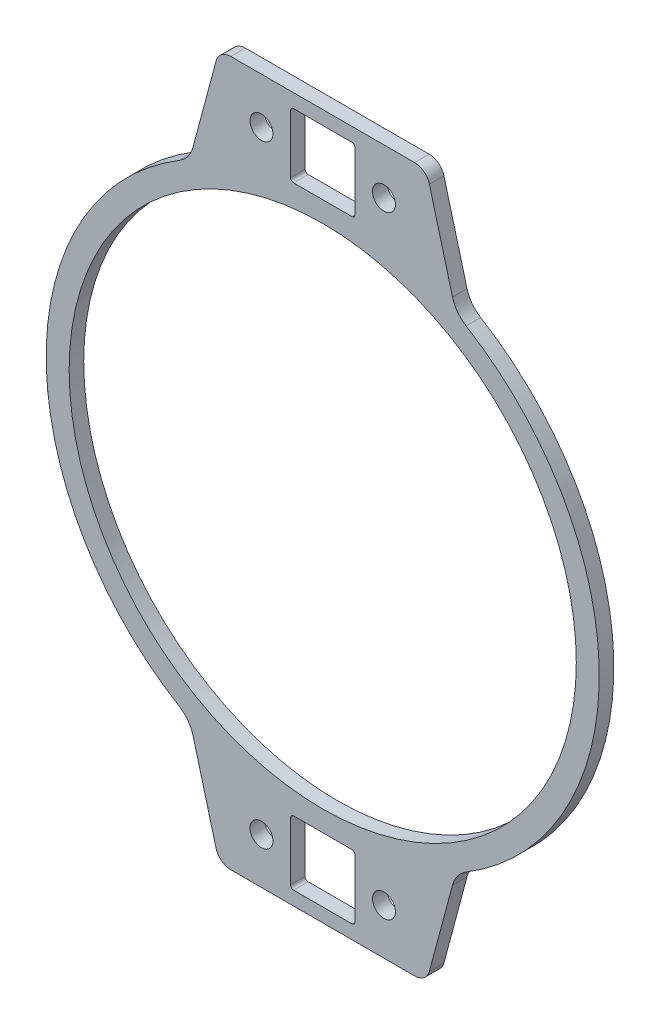
SolidWorks part; units mm, degrees
ref_plane "Front Plane" through (0, 0, 0) normal (0, 0, 1) x (1, 0, 0)
ref_plane "Top Plane" through (0, 0, 0) normal (0, 1, 0) x (1, 0, 0)
ref_plane "Right Plane" through (0, 0, 0) normal (1, 0, 0) x (0, 0, -1)
sketch "Sketch2" plane through (0, 0, -109.855) normal (0, 0, 1) x (1, 0, 0)
  line L6 (34.8296, -111.2941) -> (45.4142, -71.792)
  line L7 (-30, -115) -> (30, -115)
  line L8 (-45.4142, -71.792) -> (-34.8296, -111.2941)
  line L9 (-34.8296, 111.2941) -> (-45.4142, 71.792)
  line L10 (30, 115) -> (-30, 115)
  line L11 (45.4142, 71.792) -> (34.8296, 111.2941)
  line L12 (34.8296, -111.2941) -> (42.3672, -83.1634)
  line L13 (-30, -115) -> (30, -115)
  line L14 (-42.3672, -83.1634) -> (-34.8296, -111.2941)
  line L15 (-34.8296, 111.2941) -> (-42.3672, 83.1634)
  line L16 (30, 115) -> (-30, 115)
  line L17 (42.3672, 83.1634) -> (34.8296, 111.2941)
  line L18 (20, 100) -> (-20, 100) construction
  line L19 (20, -100) -> (-20, -100) construction
  line L20 (9.5, 89.5) -> (-9.5, 89.5)
  line L21 (10.5, 90.5) -> (10.5, 109.5)
  line L22 (9.5, 110.5) -> (-9.5, 110.5)
  line L23 (-10.5, 90.5) -> (-10.5, 109.5)
  line L24 (10.5, 89.5) -> (-10.5, 110.5) construction
  line L25 (10.5, 110.5) -> (-10.5, 89.5) construction
  line L27 (9.5, -110.5) -> (-9.5, -110.5)
  line L28 (10.5, -109.5) -> (10.5, -90.5)
  line L29 (9.5, -89.5) -> (-9.5, -89.5)
  line L30 (-10.5, -109.5) -> (-10.5, -90.5)
  line L31 (10.5, -110.5) -> (-10.5, -89.5) construction
  line L32 (10.5, -89.5) -> (-10.5, -110.5) construction
  circle A0 centre (20, -100) radius 3.75 construction
  circle A1 centre (-20, -100) radius 3.75 construction
  circle A2 centre (-20, 100) radius 3.75 construction
  circle A3 centre (20, 100) radius 3.75 construction
  circle A4 centre (20, -100) radius 3.75
  circle A5 centre (-20, -100) radius 3.75
  circle A6 centre (-20, 100) radius 3.75
  circle A7 centre (20, 100) radius 3.75
  arc A8 (-46.8394, 77.2021) -> (-46.8394, -77.2021) centre (0, 0) ccw
  circle A9 centre (0, 0) radius 82.8
  arc A10 (45.4142, 71.792) -> (49.1228, 66.3435) centre (55.0734, 74.3802) ccw
  arc A11 (49.1228, -66.3435) -> (49.1228, 66.3435) centre (0, 0) ccw
  arc A12 (49.1228, -66.3435) -> (45.4142, -71.792) centre (55.0734, -74.3802) ccw
  arc A13 (30, -115) -> (34.8296, -111.2941) centre (30, -110) ccw
  arc A14 (-34.8296, -111.2941) -> (-30, -115) centre (-30, -110) ccw
  arc A15 (-45.4142, -71.792) -> (-49.1228, -66.3435) centre (-55.0734, -74.3802) ccw
  arc A16 (-49.1228, 66.3435) -> (-49.1228, -66.3435) centre (0, 0) ccw
  arc A17 (-49.1228, 66.3435) -> (-45.4142, 71.792) centre (-55.0734, 74.3802) ccw
  arc A18 (-30, 115) -> (-34.8296, 111.2941) centre (-30, 110) ccw
  arc A19 (34.8296, 111.2941) -> (30, 115) centre (30, 110) ccw
  arc A23 (30, -115) -> (34.8296, -111.2941) centre (30, -110) ccw
  arc A24 (-34.8296, -111.2941) -> (-30, -115) centre (-30, -110) ccw
  arc A28 (-30, 115) -> (-34.8296, 111.2941) centre (-30, 110) ccw
  arc A29 (34.8296, 111.2941) -> (30, 115) centre (30, 110) ccw
  arc A30 (46.8394, -77.2021) -> (46.8394, 77.2021) centre (0, 0) ccw
  arc A31 (42.3672, -83.1634) -> (46.8394, -77.2021) centre (52.0265, -85.7516) cw
  arc A32 (-46.8394, -77.2021) -> (-42.3672, -83.1634) centre (-52.0265, -85.7516) cw
  arc A33 (-46.8394, 77.2021) -> (-42.3672, 83.1634) centre (-52.0265, 85.7516) ccw
  arc A34 (46.8394, 77.2021) -> (42.3672, 83.1634) centre (52.0265, 85.7516) cw
  arc A45 (9.5, 89.5) -> (10.5, 90.5) centre (9.5, 90.5) ccw
  arc A46 (-9.5, 89.5) -> (-10.5, 90.5) centre (-9.5, 90.5) cw
  arc A47 (-9.5, 110.5) -> (-10.5, 109.5) centre (-9.5, 109.5) ccw
  arc A48 (10.5, 109.5) -> (9.5, 110.5) centre (9.5, 109.5) ccw
  arc A49 (-9.5, -110.5) -> (-10.5, -109.5) centre (-9.5, -109.5) cw
  arc A50 (9.5, -110.5) -> (10.5, -109.5) centre (9.5, -109.5) ccw
  arc A51 (-9.5, -89.5) -> (-10.5, -90.5) centre (-9.5, -90.5) ccw
  arc A52 (10.5, -90.5) -> (9.5, -89.5) centre (9.5, -90.5) ccw
  point P47 (43.4384, -79.1656)
  point P54 (0, 100)
  point P71 (0, -100)
  dimension "D2" = 165.6
  dimension "D3" = 7.5
  dimension "D4" = 10
  dimension "D6" = 1
  dimension "D7" = 1
  dimension "D5" = 21
  dimension "D1" = 0
extrude "Boss-Extrude1" add sketch "Sketch2" along normal blind 4.7498
